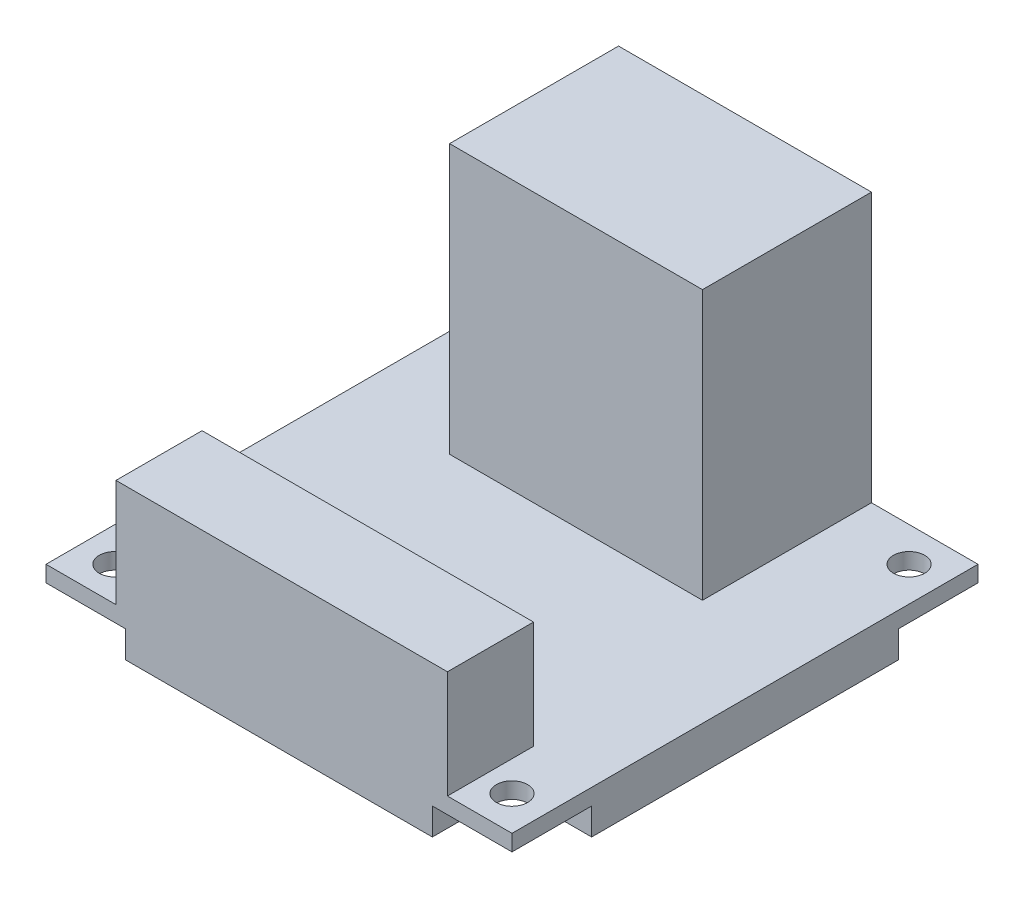
SolidWorks part; units mm, degrees
ref_plane "Front Plane" through (0, 0, 0) normal (0, 0, 1) x (1, 0, 0)
ref_plane "Top Plane" through (0, 0, 0) normal (0, 1, 0) x (1, 0, 0)
ref_plane "Right Plane" through (0, 0, 0) normal (1, 0, 0) x (0, 0, -1)
sketch "Sketch1" plane through (0, 0, 0) normal (0, 1, 0) x (1, 0, 0)
  line L0 (3.2, 38.65) -> (3.2, 4.65) construction
  line L1 (0, 0) -> (43.3, 0)
  line L2 (0, 0) -> (0, 43.3)
  line L3 (0, 43.3) -> (43.3, 43.3)
  line L4 (43.3, 0) -> (43.3, 43.3)
  line L5 (4.65, 3.2) -> (38.65, 3.2) construction
  circle A0 centre (3.2, 3.2) radius 1.45
  circle A1 centre (3.2, 40.1) radius 1.45
  circle A2 centre (40.1, 40.1) radius 1.45
  circle A3 centre (40.1, 3.2) radius 1.45
  point P13 (21.65, 3.2)
  point P16 (21.65, 0)
  point P19 (3.2, 21.65)
  point P20 (0, 21.65)
  dimension "D2" = 2.9
  dimension "D1" = 43.3
  dimension "D3" = 34
extrude "Boss-Extrude1" add sketch "Sketch1" along normal blind 1.5
sketch "Sketch2" plane through (0, 0, 0) normal (0, -1, 0) x (1, 0, 0)
  line L0 (0, -35.9) -> (0, -7.4)
  line L1 (0, -43.3) -> (0, 0) construction
  line L2 (0, -7.4) -> (7.4, -7.4)
  line L3 (7.4, -7.4) -> (7.4, 0)
  line L4 (0, 0) -> (43.3, 0) construction
  line L5 (7.4, 0) -> (35.9, 0)
  line L6 (35.9, 0) -> (35.9, -7.4)
  line L7 (35.9, -7.4) -> (43.3, -7.4)
  line L8 (43.3, 0) -> (43.3, -43.3) construction
  line L9 (43.3, -7.4) -> (43.3, -35.9)
  line L10 (43.3, -35.9) -> (35.9, -35.9)
  line L11 (35.9, -35.9) -> (35.9, -43.3)
  line L12 (35.9, -43.3) -> (7.4, -43.3)
  line L13 (43.3, -43.3) -> (0, -43.3) construction
  line L14 (7.4, -43.3) -> (7.4, -35.9)
  line L15 (7.4, -35.9) -> (0, -35.9)
  dimension "D1" = 28.5
extrude "Boss-Extrude2" add sketch "Sketch2" along normal blind 2.5
sketch "Sketch3" plane through (0, 1.5, 0) normal (0, 1, 0) x (1, 0, 0)
  line L0 (0, 0) -> (43.3, 0) construction
  line L1 (6.5, 0) -> (37.3, 0)
  line L2 (6.5, 0) -> (6.5, 8)
  line L3 (6.5, 8) -> (37.3, 8)
  line L4 (37.3, 0) -> (37.3, 8)
  dimension "D1" = 6
  dimension "D2" = 6.5
  dimension "D3" = 8
extrude "Boss-Extrude3" add sketch "Sketch3" along normal blind 10
sketch "Sketch4" plane through (0, 1.5, 0) normal (0, 1, 0) x (1, 0, 0)
  line L0 (43.3, 43.3) -> (0, 43.3) construction
  line L1 (33.4, 43.3) -> (9.9, 43.3)
  line L2 (33.4, 43.3) -> (33.4, 27.6)
  line L3 (33.4, 27.6) -> (9.9, 27.6)
  line L4 (9.9, 43.3) -> (9.9, 27.6)
  dimension "D1" = 9.9
  dimension "D2" = 9.9
  dimension "D3" = 15.7
extrude "Boss-Extrude4" add sketch "Sketch4" along normal blind 25
